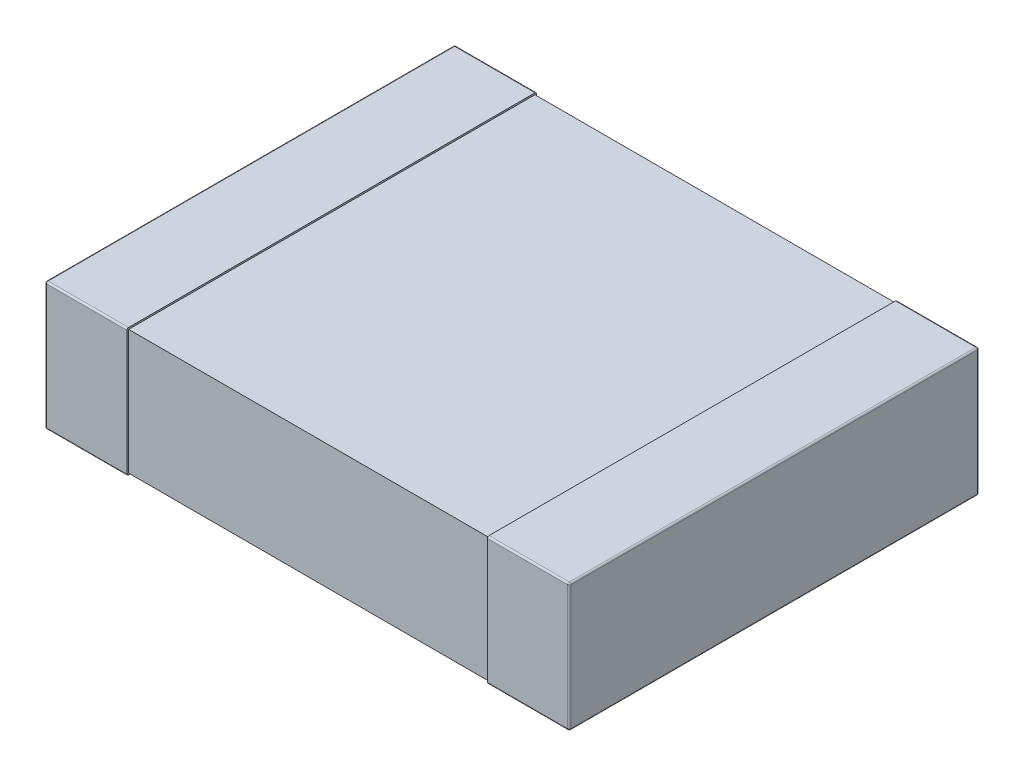
SolidWorks part; units mm, degrees
ref_plane "Front Plane" through (0, 0, 0) normal (0, 0, 1) x (1, 0, 0)
ref_plane "Top Plane" through (0, 0, 0) normal (0, 1, 0) x (1, 0, 0)
ref_plane "Right Plane" through (0, 0, 0) normal (1, 0, 0) x (0, 0, -1)
sketch "Sketch1" plane through (0, 0, 0) normal (0, 1, 0) x (1, 0, 0)
  line L0 (0, 0.15) -> (0, -0.15) construction
  line L1 (-1.6, 0) -> (0, 0) construction
  line L3 (-1.6, 1.25) -> (-1.1, 1.25)
  line L4 (-1.6, 1.25) -> (-1.6, -1.25)
  line L5 (-1.6, -1.25) -> (-1.1, -1.25)
  line L6 (-1.1, 1.25) -> (-1.1, -1.25)
  dimension "BANDWIDTH" = 0.5
  dimension "WIDTH" = 2.5
  dimension "LENGTH-HALF" = 1.6
extrude "THICKNESS" add sketch "Sketch1" along normal mid plane 0.78
fillet "Fillet1" radius 0.01 8 edges at (-1.6, -0.39, 0) (-1.35, -0.39, -1.25) (-1.6, 0, -1.25) (-1.35, -0.39, 1.25) (-1.6, 0, 1.25) (-1.6, 0.39, 0) (-1.35, 0.39, -1.25) (-1.35, 0.39, 1.25)
sketch "Sketch2" plane through (0, 0, 0) normal (1, 0, 0) x (0, 0, -1)
  line L0 (0, 0.39) -> (0, -0.39) construction
  line L1 (-1.24, 0.38) -> (1.24, 0.38)
  line L2 (-1.24, 0.38) -> (-1.24, -0.38)
  line L3 (-1.24, -0.38) -> (1.24, -0.38)
  line L4 (1.24, 0.38) -> (1.24, -0.38)
  line L5 (-1.24, 0.39) -> (1.24, 0.39) construction
  line L6 (-1.24, -0.39) -> (1.24, -0.39) construction
  line L7 (-1.25, 0) -> (1.25, 0) construction
  line L8 (-1.25, 0.38) -> (-1.25, -0.38) construction
  line L9 (1.25, 0.38) -> (1.25, -0.38) construction
  dimension "D1" = 0.01
  dimension "D2" = 0.01
extrude "Boss-Extrude2" add sketch "Sketch2" against normal up to surface (1.1 mm away) up to face at (-1.1, 0, 0)
mirror "Mirror3" about plane through (0, 0, 0) normal (1, 0, 0) of "Boss-Extrude2", "Fillet1", "THICKNESS"
